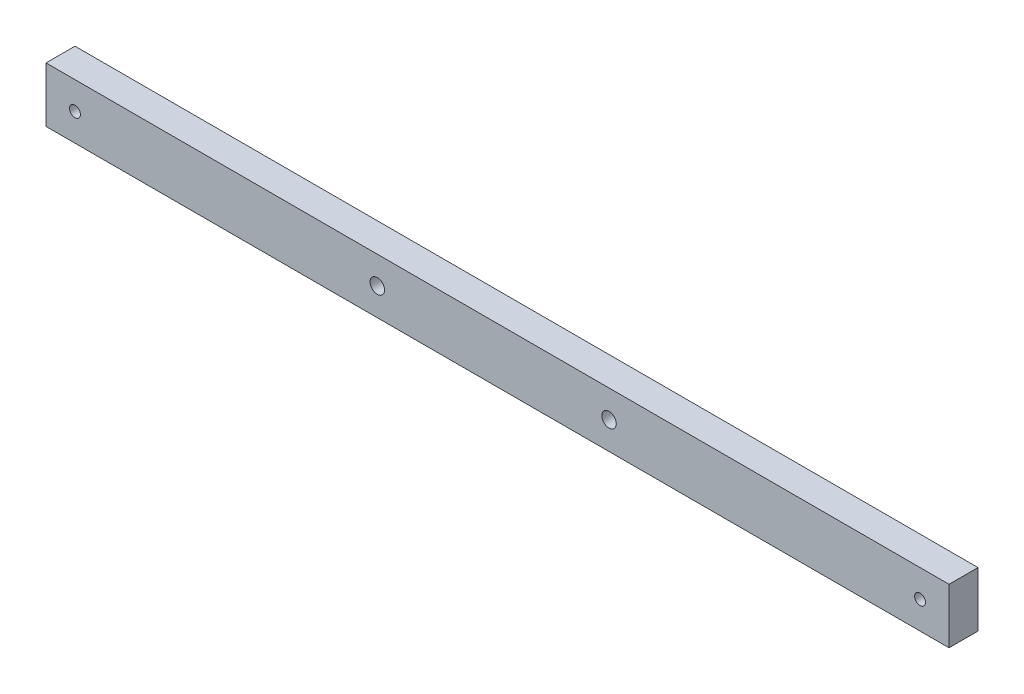
SolidWorks part; units mm, degrees
ref_plane "前视基准面" through (0, 0, 0) normal (0, 0, 1) x (1, 0, 0)
ref_plane "上视基准面" through (0, 0, 0) normal (0, 1, 0) x (1, 0, 0)
ref_plane "右视基准面" through (0, 0, 0) normal (1, 0, 0) x (0, 0, -1)
sketch "草图2" plane through (0, 0, 0) normal (0, 0, 1) x (1, 0, 0)
  line L0 (0, 0) -> (0, -11.1015) construction
  line L1 (-31.175, 1.9) -> (31.175, 1.9)
  line L2 (-31.175, 1.9) -> (-31.175, -1.9)
  line L3 (-31.175, -1.9) -> (31.175, -1.9)
  line L4 (31.175, 1.9) -> (31.175, -1.9)
  line L5 (-31.175, 1.9) -> (31.175, -1.9) construction
  line L6 (-31.175, -1.9) -> (31.175, 1.9) construction
  circle A1 centre (7.7, 0) radius 0.5
  circle A3 centre (-8.3, 0) radius 0.5
  point P0 (0, 0)
  dimension "D3" = 1
  dimension "D5" = 1
  dimension "D4" = 7.7
  dimension "D1" = 3.8
  dimension "D2" = 62.35
  dimension "D7" = 8.3
extrude "凸台-拉伸1" add sketch "草图2" along normal blind 2
sketch "草图3" plane through (0, 0, 0) normal (0, 0, -1) x (-1, 0, 0)
  line L0 (31.175, 1.9) -> (31.175, -1.9) construction
  line L1 (31.175, -1.9) -> (-31.175, -1.9) construction
  line L2 (-31.175, 1.9) -> (31.175, 1.9) construction
  line L3 (29.175, -1.9) -> (29.175, 1.9) construction
  line L4 (-31.175, 0) -> (-29.175, 0) construction
  line L5 (-31.175, -1.9) -> (-31.175, 1.9) construction
  circle A0 centre (29.175, 0) radius 0.375
  circle A1 centre (-29.175, 0) radius 0.375
  dimension "D1" = 0.75
  dimension "D3" = 0.75
  dimension "D2" = 2
  dimension "D4" = 2
extrude "切除-拉伸1" cut sketch "草图3" against normal up to next
